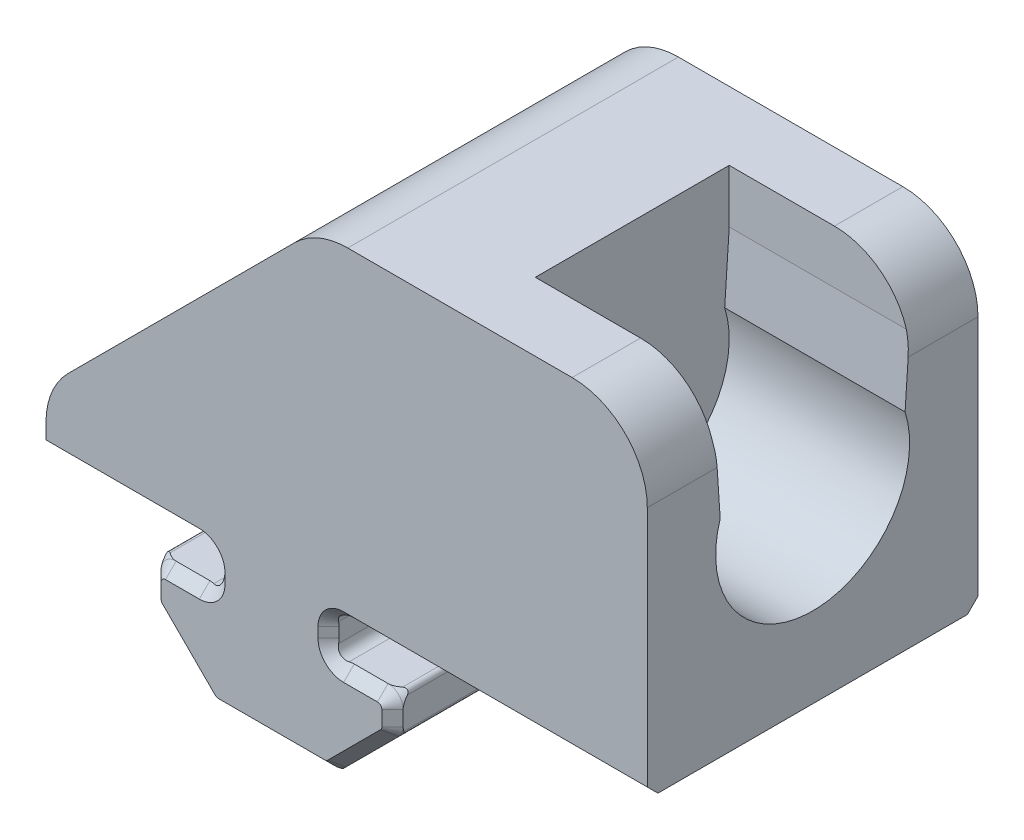
SolidWorks part; units mm, degrees
ref_plane "Front Plane" through (0, 0, 0) normal (0, 0, 1) x (1, 0, 0)
ref_plane "Top Plane" through (0, 0, 0) normal (0, 1, 0) x (1, 0, 0)
ref_plane "Right Plane" through (0, 0, 0) normal (1, 0, 0) x (0, 0, -1)
sketch "Sketch1" plane through (0, 0, 0) normal (0, 0, 1) x (1, 0, 0)
  line L0 (12.9999, 9.1653) -> (4.5, 9.1653)
  line L1 (-4.5, 9.1653) -> (-12.9999, 9.1653)
  line L2 (4, 8.6653) -> (4, 7.4078)
  line L3 (4.5, 6.9078) -> (7.7325, 6.9078)
  line L4 (8.1035, 4.072) -> (4.178, 0.1464)
  line L5 (3.8245, 0) -> (-3.8245, 0)
  line L6 (-4.178, 0.1464) -> (-8.1035, 4.072)
  line L7 (-8.25, 4.4255) -> (-8.25, 6.4081)
  line L8 (-7.7325, 6.9078) -> (-4.5, 6.9078)
  line L9 (-4, 7.4078) -> (-4, 8.6653)
  line L10 (8.25, 6.4081) -> (8.25, 4.4255)
  arc A0 (14.9999, 7.1653) -> (12.9999, 9.1653) centre (12.9999, 7.1653) ccw
  arc A1 (-12.9999, 9.1653) -> (-14.9999, 7.1653) centre (-12.9999, 7.1653) ccw
  arc A2 (4.5, 9.1653) -> (4, 8.6653) centre (4.5, 8.6653) ccw
  arc A3 (4, 7.4078) -> (4.5, 6.9078) centre (4.5, 7.4078) ccw
  arc A4 (8.25, 6.4081) -> (7.7325, 6.9078) centre (7.75, 6.4081) ccw
  arc A5 (8.1035, 4.072) -> (8.25, 4.4255) centre (7.75, 4.4255) ccw
  arc A6 (3.8245, 0) -> (4.178, 0.1464) centre (3.8245, 0.5) ccw
  arc A7 (-4.178, 0.1464) -> (-3.8245, 0) centre (-3.8245, 0.5) ccw
  arc A8 (-8.25, 4.4255) -> (-8.1035, 4.072) centre (-7.75, 4.4255) ccw
  arc A9 (-7.7325, 6.9078) -> (-8.25, 6.4081) centre (-7.75, 6.4081) ccw
  arc A10 (-4.5, 6.9078) -> (-4, 7.4078) centre (-4.5, 7.4078) ccw
  arc A11 (-4, 8.6653) -> (-4.5, 9.1653) centre (-4.5, 8.6653) ccw
  point P36 (0, 0)
  point P37 (2.4964, -7.8852)
  dimension "D1" = 2
sketch "Sketch2" plane through (0, 0, 0) normal (0, 0, 1) x (1, 0, 0)
  line L0 (14.9999, 31.1653) -> (24.9999, 31.1653)
  line L1 (24.9999, 31.1653) -> (24.9999, 9.3653)
  line L2 (24.9999, 9.3653) -> (14.9999, 9.3653)
  line L112 (-12.9999, 9.3653) -> (-14.9999, 9.3653)
  line L113 (-14.9999, 9.3653) -> (-14.9999, 7.1653) construction
  line L114 (12.9999, 9.3653) -> (14.9999, 9.3653)
  line L115 (14.9999, 9.3653) -> (14.9999, 7.1653) construction
  line L116 (-14.9999, 9.3653) -> (-14.9999, 31.1653)
  line L117 (-14.9999, 31.1653) -> (14.9999, 31.1653)
  line L118 (14.9999, 31.1653) -> (14.9999, 9.3653) construction
  line L119 (-4.5, 9.1653) -> (-12.9999, 9.1653) construction
  line L123 (-4.5, 9.3653) -> (-12.9999, 9.3653)
  line L124 (12.9999, 9.3653) -> (4.5, 9.3653)
  line L125 (3.8, 8.6653) -> (3.8, 7.4078)
  line L126 (4.5, 6.7078) -> (7.7365, 6.7078)
  line L127 (8.05, 6.4081) -> (8.05, 4.4255)
  line L128 (7.9621, 4.2134) -> (4.0366, 0.2879)
  line L129 (3.8245, 0.2) -> (-3.8245, 0.2)
  line L130 (-4.0366, 0.2879) -> (-7.9621, 4.2134)
  line L131 (-8.05, 4.4255) -> (-8.05, 6.4081)
  line L132 (-7.7365, 6.7078) -> (-4.5, 6.7078)
  line L133 (-3.8, 7.4078) -> (-3.8, 8.6653)
  line L134 (-4.5, 9.3653) -> (-12.9999, 9.3653)
  line L135 (12.9999, 9.3653) -> (4.5, 9.3653)
  line L136 (3.8, 8.6653) -> (3.8, 7.4078)
  line L137 (4.5, 6.7078) -> (7.7365, 6.7078)
  line L138 (8.05, 6.4081) -> (8.05, 4.4255)
  line L139 (7.9621, 4.2134) -> (4.0366, 0.2879)
  line L140 (3.8245, 0.2) -> (-3.8245, 0.2)
  line L141 (-4.0366, 0.2879) -> (-7.9621, 4.2134)
  line L142 (-8.05, 4.4255) -> (-8.05, 6.4081)
  line L143 (-7.7365, 6.7078) -> (-4.5, 6.7078)
  line L144 (-3.8, 7.4078) -> (-3.8, 8.6653)
  arc A131 (4.5, 9.3653) -> (3.8, 8.6653) centre (4.5, 8.6653) ccw
  arc A132 (3.8, 7.4078) -> (4.5, 6.7078) centre (4.5, 7.4078) ccw
  arc A133 (8.05, 6.4081) -> (7.7365, 6.7078) centre (7.75, 6.4081) ccw
  arc A134 (7.9621, 4.2134) -> (8.05, 4.4255) centre (7.75, 4.4255) ccw
  arc A135 (3.8245, 0.2) -> (4.0366, 0.2879) centre (3.8245, 0.5) ccw
  arc A136 (-4.0366, 0.2879) -> (-3.8245, 0.2) centre (-3.8245, 0.5) ccw
  arc A137 (-8.05, 4.4255) -> (-7.9621, 4.2134) centre (-7.75, 4.4255) ccw
  arc A138 (-7.7365, 6.7078) -> (-8.05, 6.4081) centre (-7.75, 6.4081) ccw
  arc A139 (-4.5, 6.7078) -> (-3.8, 7.4078) centre (-4.5, 7.4078) ccw
  arc A140 (-3.8, 8.6653) -> (-4.5, 9.3653) centre (-4.5, 8.6653) ccw
  arc A141 (4.5, 9.3653) -> (3.8, 8.6653) centre (4.5, 8.6653) ccw
  arc A142 (3.8, 7.4078) -> (4.5, 6.7078) centre (4.5, 7.4078) ccw
  arc A143 (8.05, 6.4081) -> (7.7365, 6.7078) centre (7.75, 6.4081) ccw
  arc A144 (7.9621, 4.2134) -> (8.05, 4.4255) centre (7.75, 4.4255) ccw
  arc A145 (3.8245, 0.2) -> (4.0366, 0.2879) centre (3.8245, 0.5) ccw
  arc A146 (-4.0366, 0.2879) -> (-3.8245, 0.2) centre (-3.8245, 0.5) ccw
  arc A147 (-8.05, 4.4255) -> (-7.9621, 4.2134) centre (-7.75, 4.4255) ccw
  arc A148 (-7.7365, 6.7078) -> (-8.05, 6.4081) centre (-7.75, 6.4081) ccw
  arc A149 (-4.5, 6.7078) -> (-3.8, 7.4078) centre (-4.5, 7.4078) ccw
  arc A150 (-3.8, 8.6653) -> (-4.5, 9.3653) centre (-4.5, 8.6653) ccw
  dimension "D2" = 22
  dimension "D3" = 10
  dimension "D1" = 0.2
extrude "Boss-Extrude1" add sketch "Sketch2" along normal blind 22
sketch "Sketch3" plane through (24.9999, 0, 0) normal (1, 0, 0) x (0, 0, -1)
  line L0 (-11, 31.1653) -> (-11, 21.1653) construction
  line L1 (-17.45, 31.1653) -> (-4.55, 31.1653)
  line L2 (-17.45, 21.1653) -> (-17.45, 31.1653) construction
  line L3 (-17.45, 31.1653) -> (-4.55, 31.1653) construction
  line L4 (-4.55, 31.1653) -> (-4.55, 21.1653) construction
  line L5 (-17.15, 23.1095) -> (-17.45, 27.6153)
  line L6 (-4.85, 23.1095) -> (-4.55, 27.6153)
  line L7 (-4.55, 27.6153) -> (-17.45, 27.6153) construction
  line L8 (-17.45, 27.6153) -> (-17.45, 31.1653)
  line L9 (-4.55, 27.6153) -> (-4.55, 31.1653)
  line L11 (-22, 31.1653) -> (0, 31.1653) construction
  arc A0 (-17.15, 23.1095) -> (-4.85, 23.1095) centre (-11, 21.1653) ccw
  dimension "D1" = 12.9
  dimension "D2" = 10
  dimension "D3" = 0.3
  dimension "D4" = 0.3
extrude "Cut-Extrude1" cut sketch "Sketch3" against normal blind 12
chamfer "Chamfer1" distance 18 angle 45 1 edges at (-14.9999, 31.1653, 11)
fillet "Fillet1" radius 5 2 edges at (-14.9999, 13.1653, 11) (3.0001, 31.1653, 11)
fillet "Fillet2" radius 5 2 edges at (24.9999, 31.1653, 2.275) (24.9999, 31.1653, 19.725)
ref_plane "Plane1" through (0, 0, 0) normal (-1, 0, 0) x (0, 0, 1)
sketch "Sketch4" plane through (-14.9999, 0, 0) normal (-1, 0, 0) x (0, 0, 1)
  line L0 (22, 10.0724) -> (22.7071, 9.3653)
  line L1 (22, 11.0942) -> (22, 9.3653) construction
  line L2 (22, 10.0724) -> (21.2929, 9.3653)
  line L3 (22, 9.3653) -> (0, 9.3653) construction
  line L4 (22.7071, 9.3653) -> (22, 8.6582)
  line L5 (22, 10.0724) -> (22.7071, 10.7795) construction
  line L6 (22, 8.6582) -> (21.2929, 9.3653) construction
  line L7 (21.2929, 9.3653) -> (22.7071, 9.3653) construction
  line L8 (22, 10.0724) -> (22, 8.6582) construction
  line L9 (22.7071, 10.7795) -> (22.7071, 9.3653) construction
  line L10 (21.2929, 9.3653) -> (20.7763, 8.9631)
  line L12 (20.7763, 8.9631) -> (22, 8.6582)
  point P0 (22, 9.3653)
  point P2 (20.7763, 8.9631)
  point P12 (22, 9.3653)
  dimension "D1" = 1
sketch "Sketch43" plane through (0, 0, 22) normal (0, 0, 1) x (1, 0, 0)
  line L0 (-14.9999, 9.3653) -> (-4.8, 9.3653)
  line L2 (-3.8, 8.3653) -> (-3.8, 7.7078)
  line L3 (-7.05, 6.7078) -> (-4.8, 6.7078)
  line L4 (-8.05, 5.7078) -> (-8.05, 4.7155)
  line L5 (-7.7571, 4.0084) -> (-4.2416, 0.4929)
  line L6 (-3.5345, 0.2) -> (3.5345, 0.2)
  line L7 (14.9999, 9.3653) -> (24.9999, 9.3653)
  line L8 (24.9999, 9.3653) -> (24.9999, 26.1653) construction
  line L9 (4.5, 9.3653) -> (24.9999, 9.3653) construction
  line L10 (-3.8245, 0.2) -> (3.8245, 0.2) construction
  line L11 (-7.9621, 4.2134) -> (-4.0366, 0.2879) construction
  line L12 (-8.05, 6.4081) -> (-8.05, 4.4255) construction
  line L13 (-4.5, 6.7078) -> (-7.7365, 6.7078) construction
  line L14 (-3.8, 8.6653) -> (-3.8, 7.4078) construction
  line L15 (-14.9999, 9.3653) -> (-4.5, 9.3653) construction
  line L16 (0, 4.0409) -> (0, -4.2786) construction
  line L17 (0, 12.1316) -> (0, -12.1316) construction
  line L18 (-14.9999, 11.0942) -> (-14.9999, 9.3653) construction
  line L19 (7.7571, 4.0084) -> (4.2416, 0.4929)
  line L20 (8.05, 5.7078) -> (8.05, 4.7155)
  line L21 (7.05, 6.7078) -> (4.8, 6.7078)
  line L22 (3.8, 8.3653) -> (3.8, 7.7078)
  line L23 (14.9999, 9.3653) -> (4.8, 9.3653)
  arc A0 (3.8, 8.3653) -> (4.8, 9.3653) centre (4.8, 8.3653) cw
  arc A1 (4.8, 6.7078) -> (3.8, 7.7078) centre (4.8, 7.7078) cw
  arc A2 (8.05, 5.7078) -> (7.05, 6.7078) centre (7.05, 5.7078) ccw
  arc A3 (7.7571, 4.0084) -> (8.05, 4.7155) centre (7.05, 4.7155) ccw
  arc A4 (4.2416, 0.4929) -> (3.5345, 0.2) centre (3.5345, 1.2) cw
  arc A5 (-3.5345, 0.2) -> (-4.2416, 0.4929) centre (-3.5345, 1.2) cw
  arc A6 (-7.7571, 4.0084) -> (-8.05, 4.7155) centre (-7.05, 4.7155) cw
  arc A7 (-8.05, 5.7078) -> (-7.05, 6.7078) centre (-7.05, 5.7078) cw
  arc A8 (-4.8, 6.7078) -> (-3.8, 7.7078) centre (-4.8, 7.7078) ccw
  arc A9 (-3.8, 8.3653) -> (-4.8, 9.3653) centre (-4.8, 8.3653) ccw
  point P11 (0, 0)
  point P21 (0, 0.2)
  point P39 (0, 0)
  point P41 (3.8, 9.3653)
  point P44 (3.8, 6.7078)
  point P47 (8.05, 6.7078)
  point P50 (8.05, 4.3013)
  point P53 (3.9487, 0.2)
  point P56 (-3.9487, 0.2)
  point P59 (-8.05, 4.3013)
  point P62 (-8.05, 6.7078)
  point P65 (-3.8, 6.7078)
  point P68 (-3.8, 9.3653)
  dimension "D1" = 1
sweep "Cut-Sweep7" cut profiles "Sketch4" path "Sketch43"
ref_plane "Plane2" through (0, 0, 11) normal (0, 0, -1) x (-1, 0, 0)
mirror "Mirror1" about plane through (0, 0, 11) normal (0, 0, -1) of "Cut-Sweep7"
